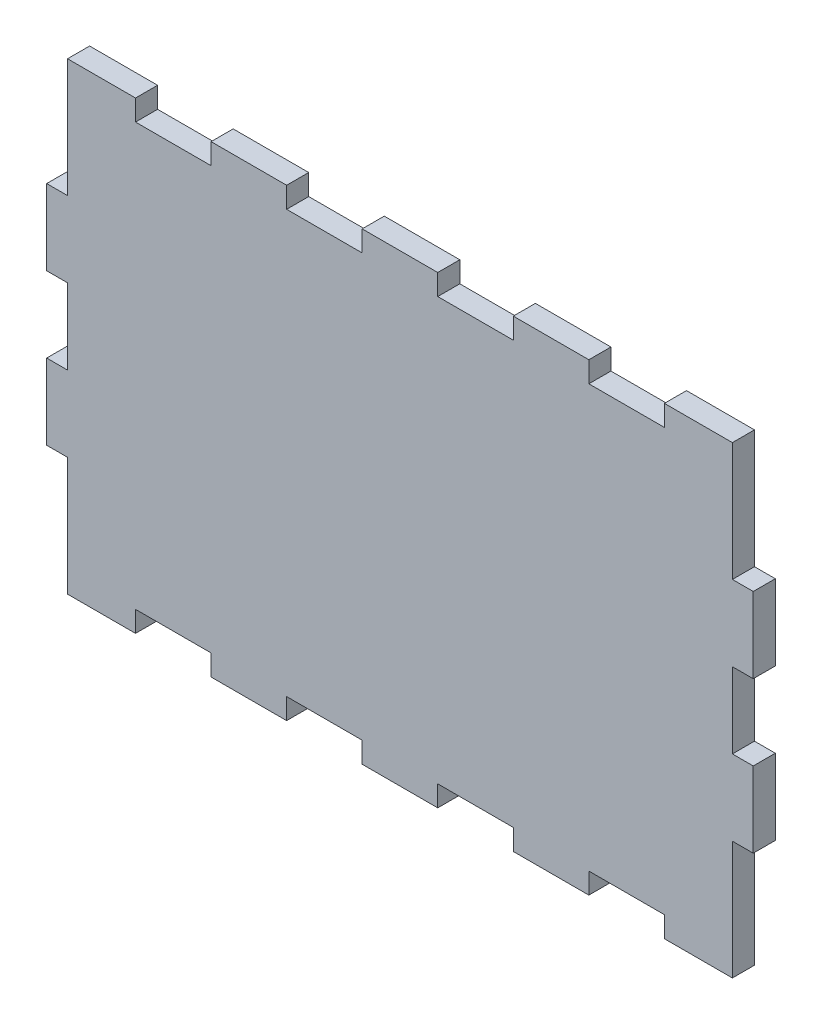
SolidWorks part; units mm, degrees
ref_plane "Front Plane" through (0, 0, 0) normal (0, 0, 1) x (1, 0, 0)
ref_plane "Top Plane" through (0, 0, 0) normal (0, 1, 0) x (1, 0, 0)
ref_plane "Right Plane" through (0, 0, 0) normal (1, 0, 0) x (0, 0, -1)
sketch "Sketch3" plane through (0, 0, 0) normal (0, 0, 1) x (1, 0, 0)
  line L54 (25.5461, 133.35) -> (5.9944, 133.35)
  line L55 (5.9944, 133.35) -> (5.9944, 99.2695)
  line L56 (5.9944, 99.2695) -> (0, 99.2695)
  line L57 (0, 99.2695) -> (0, 77.5398)
  line L58 (0, 77.5398) -> (5.9944, 77.5398)
  line L59 (5.9944, 77.5398) -> (5.9944, 55.8102)
  line L60 (5.9944, 55.8102) -> (0, 55.8102)
  line L61 (0, 55.8102) -> (0, 34.0804)
  line L62 (0, 34.0804) -> (5.9944, 34.0804)
  line L63 (5.9944, 34.0804) -> (5.9944, 12.3508)
  line L64 (5.9944, 12.3508) -> (5.9944, 0)
  line L65 (5.9944, 0) -> (25.5461, 0)
  line L66 (25.5461, 0) -> (25.5461, 5.9944)
  line L67 (25.5461, 5.9944) -> (47.2757, 5.9944)
  line L68 (47.2757, 5.9944) -> (47.2757, 0)
  line L69 (47.2757, 0) -> (69.0054, 0)
  line L70 (69.0054, 0) -> (69.0054, 5.9944)
  line L71 (69.0054, 5.9944) -> (90.7352, 5.9944)
  line L72 (90.7352, 5.9944) -> (90.7352, 0)
  line L73 (90.7352, 0) -> (112.4648, 0)
  line L74 (112.4648, 0) -> (112.4648, 5.9944)
  line L75 (112.4648, 5.9944) -> (134.1945, 5.9944)
  line L76 (134.1945, 5.9944) -> (134.1945, 0)
  line L77 (134.1945, 0) -> (155.9242, 0)
  line L78 (155.9242, 0) -> (155.9242, 5.9944)
  line L79 (155.9242, 5.9944) -> (177.6539, 5.9944)
  line L80 (177.6539, 5.9944) -> (177.6539, 0)
  line L81 (177.6539, 0) -> (197.2056, 0)
  line L82 (197.2056, 0) -> (197.2056, 34.0804)
  line L83 (197.2056, 34.0804) -> (203.2, 34.0804)
  line L84 (203.2, 34.0804) -> (203.2, 55.8102)
  line L85 (203.2, 55.8102) -> (197.2056, 55.8102)
  line L86 (197.2056, 55.8102) -> (197.2056, 77.5398)
  line L87 (197.2056, 77.5398) -> (203.2, 77.5398)
  line L88 (203.2, 77.5398) -> (203.2, 99.2695)
  line L89 (203.2, 99.2695) -> (197.2056, 99.2695)
  line L90 (197.2056, 99.2695) -> (197.2056, 120.9993)
  line L91 (197.2056, 120.9993) -> (197.2056, 133.35)
  line L92 (197.2056, 133.35) -> (177.6539, 133.35)
  line L93 (177.6539, 133.35) -> (177.6539, 127.3556)
  line L94 (177.6539, 127.3556) -> (155.9242, 127.3556)
  line L95 (155.9242, 127.3556) -> (155.9242, 133.35)
  line L96 (155.9242, 133.35) -> (134.1945, 133.35)
  line L97 (134.1945, 133.35) -> (134.1945, 127.3556)
  line L98 (134.1945, 127.3556) -> (112.4648, 127.3556)
  line L99 (112.4648, 127.3556) -> (112.4648, 133.35)
  line L100 (112.4648, 133.35) -> (90.7352, 133.35)
  line L101 (90.7352, 133.35) -> (90.7352, 127.3556)
  line L102 (90.7352, 127.3556) -> (69.0054, 127.3556)
  line L103 (69.0054, 127.3556) -> (69.0054, 133.35)
  line L104 (69.0054, 133.35) -> (47.2757, 133.35)
  line L105 (47.2757, 133.35) -> (47.2757, 127.3556)
  line L106 (47.2757, 127.3556) -> (25.5461, 127.3556)
  line L107 (25.5461, 127.3556) -> (25.5461, 133.35)
extrude "Boss-Extrude1" add sketch "Sketch3" along normal blind 6.35 contours L54 L55 L56 L57 L58 L59 L60 L61 L62 L63 L64 L65 L66 L67 L68 L69 L70 L71 L72 L73 L74 L75 L76 L77 L78 L79 L80 L81 L82 L83 L84 L85 L86 L87 L88 L89 L90 L91 L92 L93 L94 L95 L96 L97 L98 L99 L100 L101 L102 L103 L104 L105 L106 L107
